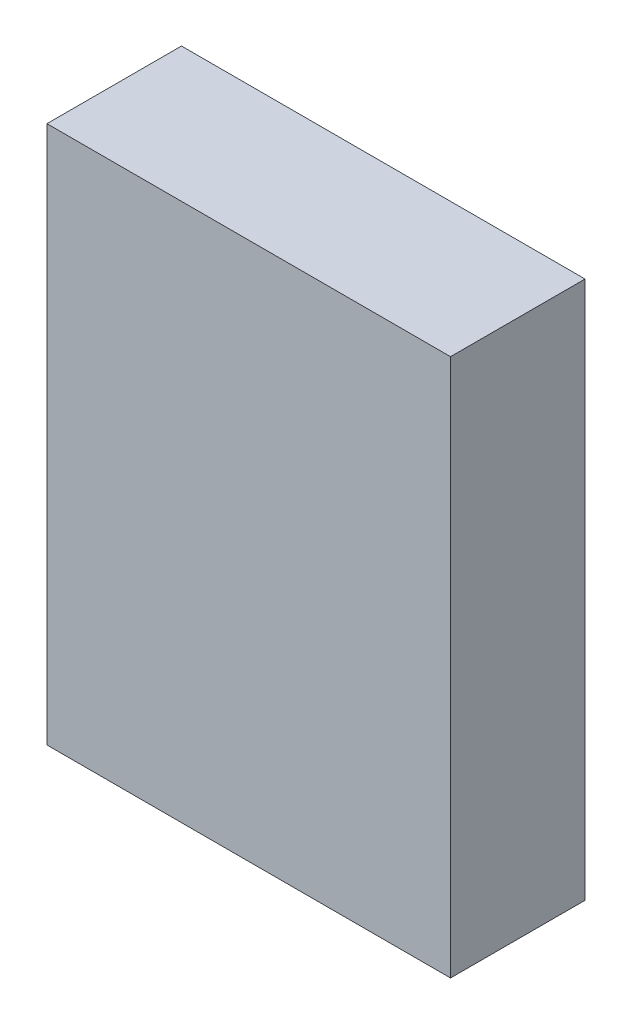
SolidWorks part; units mm, degrees
ref_plane "Alzado" through (0, 0, 0) normal (0, 0, 1) x (1, 0, 0)
ref_plane "Planta" through (0, 0, 0) normal (0, 1, 0) x (1, 0, 0)
ref_plane "Vista lateral" through (0, 0, 0) normal (1, 0, 0) x (0, 0, -1)
sketch "Croquis1" plane through (0, 0, 0) normal (0, 0, 1) x (1, 0, 0)
  line L1 (-6.5942, 16.0507) -> (8.4058, 16.0507)
  line L2 (-6.5942, 16.0507) -> (-6.5942, -3.9493)
  line L3 (-6.5942, -3.9493) -> (8.4058, -3.9493)
  line L4 (8.4058, 16.0507) -> (8.4058, -3.9493)
  dimension "D1" = 20
  dimension "D2" = 15
extrude "Saliente-Extruir1" add sketch "Croquis1" along normal blind 5
